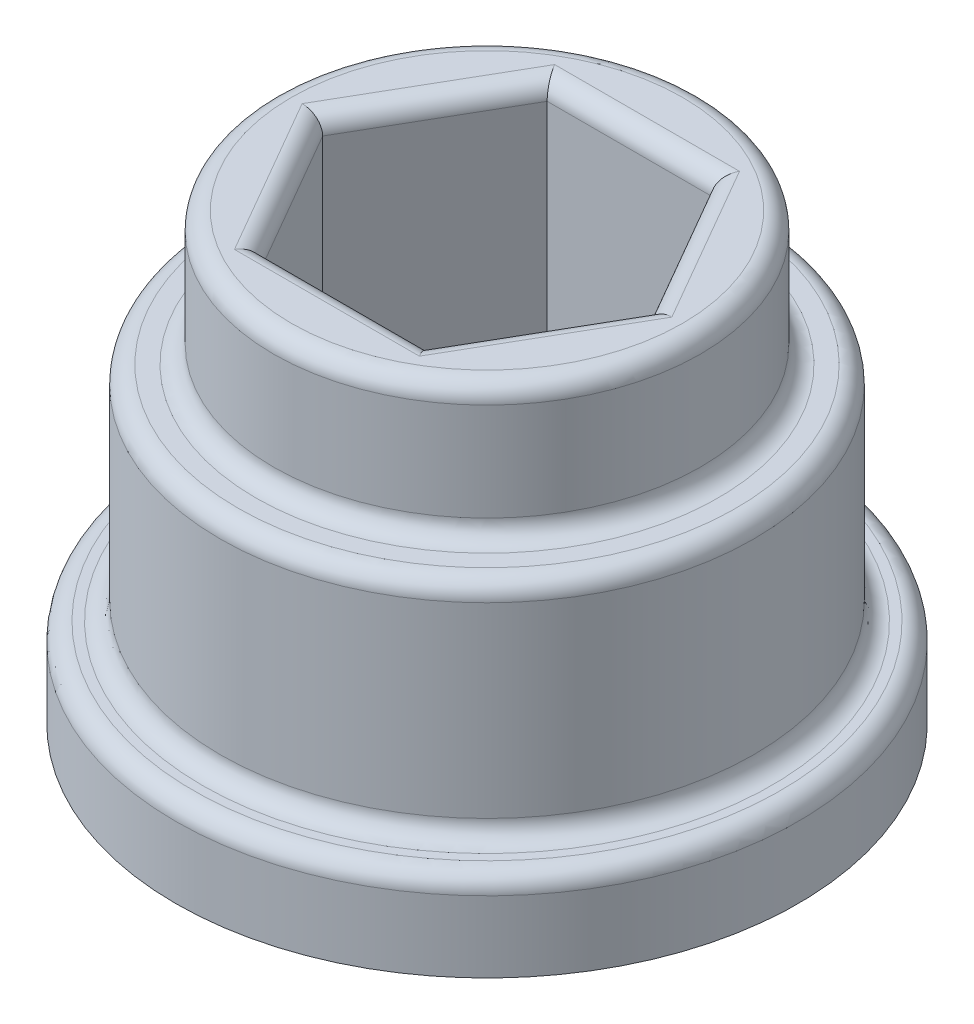
SolidWorks part; units mm, degrees
ref_plane "Front Plane" through (0, 0, 0) normal (0, 0, 1) x (1, 0, 0)
ref_plane "Top Plane" through (0, 0, 0) normal (0, 1, 0) x (1, 0, 0)
ref_plane "Right Plane" through (0, 0, 0) normal (1, 0, 0) x (0, 0, -1)
sketch "Sketch1" plane through (0, 0, 0) normal (0, 1, 0) x (1, 0, 0)
  line L1 (5.8659, 0) -> (2.9329, 5.08)
  line L2 (2.9329, 5.08) -> (-2.9329, 5.08)
  line L3 (-2.9329, 5.08) -> (-5.8659, 0)
  line L4 (-5.8659, 0) -> (-2.9329, -5.08)
  line L5 (-2.9329, -5.08) -> (2.9329, -5.08)
  line L6 (2.9329, -5.08) -> (5.8659, 0)
  circle A0 centre (0, 0) radius 5.08 construction
  circle A1 centre (0, 0) radius 9.525
  dimension "D2" = 19.05
  dimension "D1" = 10.16
extrude "Boss-Extrude1" add sketch "Sketch1" along normal blind 7.9375
sketch "Sketch2" plane through (0, 7.9375, 0) normal (0, 1, 0) x (1, 0, 0)
  line L0 (-2.9329, 5.08) -> (-5.8659, 0)
  line L1 (-5.8659, 0) -> (-2.9329, -5.08)
  line L2 (-2.9329, -5.08) -> (2.9329, -5.08)
  line L3 (2.9329, -5.08) -> (5.8659, 0)
  line L4 (5.8659, 0) -> (2.9329, 5.08)
  line L5 (2.9329, 5.08) -> (-2.9329, 5.08)
  circle A0 centre (0, 0) radius 7.62
  dimension "D1" = 15.24
extrude "Boss-Extrude2" add sketch "Sketch2" along normal blind 4.7625
sketch "Sketch3" plane through (0, 0, 0) normal (0, -1, 0) x (1, 0, 0)
  line L0 (-2.9329, 5.08) -> (2.9329, 5.08)
  line L2 (2.9329, 5.08) -> (5.8659, 0)
  line L3 (5.8659, 0) -> (2.9329, -5.08)
  line L4 (2.9329, -5.08) -> (-2.9329, -5.08)
  line L5 (-2.9329, -5.08) -> (-5.8659, 0)
  line L6 (-5.8659, 0) -> (-2.9329, 5.08)
  circle A0 centre (0, 0) radius 11.1125
  dimension "D1" = 22.225
extrude "Boss-Extrude3" add sketch "Sketch3" along normal blind 3.175 contours A0
fillet "Fillet1" radius 0.635 2 edges at (0, 0, 9.525) (0, 0, -11.1125)
fillet "Fillet3" radius 0.635 6 edges at (-4.3994, 12.7, 2.54) (0, 12.7, 5.08) (4.3994, 12.7, 2.54) (4.3994, 12.7, -2.54) (0, 12.7, -5.08) (-4.3994, 12.7, -2.54)
fillet "Fillet4" radius 0.635 3 edges at (0, 7.9375, 7.62) (0, 12.7, 7.62) (0, 7.9375, 9.525)
